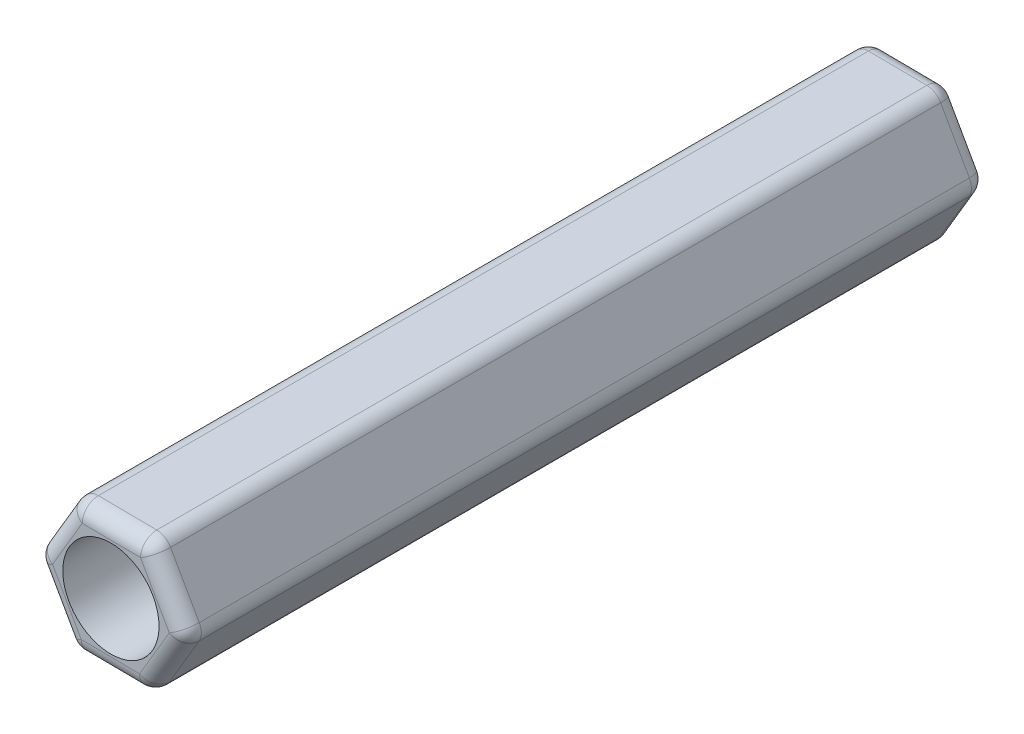
SolidWorks part; units mm, degrees
ref_plane "Alzado" through (0, 0, 0) normal (0, 0, 1) x (1, 0, 0)
ref_plane "Planta" through (0, 0, 0) normal (0, 1, 0) x (1, 0, 0)
ref_plane "Vista lateral" through (0, 0, 0) normal (1, 0, 0) x (0, 0, -1)
sketch "Croquis1" plane through (0, 0, 0) normal (0, 0, 1) x (1, 0, 0)
  line L1 (1.1782, -2.0863) -> (2.3959, -0.0228)
  line L2 (2.3959, -0.0228) -> (1.2177, 2.0635)
  line L3 (1.2177, 2.0635) -> (-1.1782, 2.0863)
  line L4 (-1.1782, 2.0863) -> (-2.3959, 0.0228)
  line L5 (-2.3959, 0.0228) -> (-1.2177, -2.0635)
  line L6 (-1.2177, -2.0635) -> (1.1782, -2.0863)
  circle A0 centre (0, 0) radius 2.075 construction
  dimension "D1" = 4.15
extrude "Saliente-Extruir1" add sketch "Croquis1" along normal blind 25
sketch "Croquis3" plane through (0, 0, 25) normal (0, 0, 1) x (1, 0, 0)
  circle A0 centre (0, 0) radius 1.5
  dimension "D1" = 3
extrude "Cortar-Extruir1" cut sketch "Croquis3" against normal blind 25
fillet "Redondeo1" radius 0.5 18 edges at (0.0198, 2.0749, 25) (1.8068, 1.0203, 25) (1.2177, 2.0635, 12.5) (1.787, -1.0546, 25) (2.3959, -0.0228, 12.5) (-0.0198, -2.0749, 25) (1.1782, -2.0863, 12.5) (-1.8068, -1.0203, 25) (-1.2177, -2.0635, 12.5) (-1.1782, 2.0863, 12.5) (-1.787, 1.0546, 25) (-2.3959, 0.0228, 12.5) (1.787, -1.0546, 0) (1.8068, 1.0203, 0) (0.0198, 2.0749, 0) (-1.787, 1.0546, 0) (-1.8068, -1.0203, 0) (-0.0198, -2.0749, 0)
